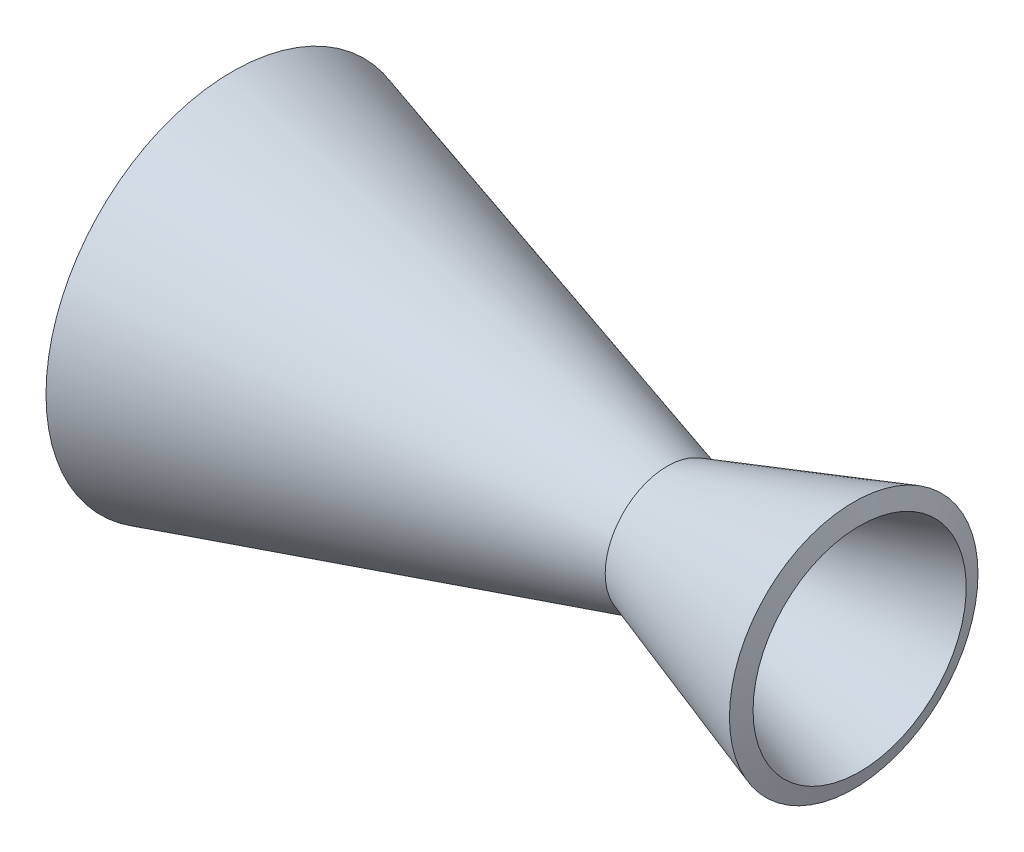
SolidWorks part; units mm, degrees
ref_plane "Front Plane" through (0, 0, 0) normal (0, 0, 1) x (1, 0, 0)
ref_plane "Top Plane" through (0, 0, 0) normal (0, 1, 0) x (1, 0, 0)
ref_plane "Right Plane" through (0, 0, 0) normal (1, 0, 0) x (0, 0, -1)
sketch "Sketch1" plane through (0, 0, 0) normal (0, 0, 1) x (1, 0, 0)
  line L5 (0, 0) -> (95.3663, 0) construction
  line L11 (0, 30) -> (70, 10)
  line L12 (70, 10) -> (100, 20)
  dimension "D1" = 30
revolve "Revolve-Thin1" add sketch "Sketch1" angle 360 about L5
